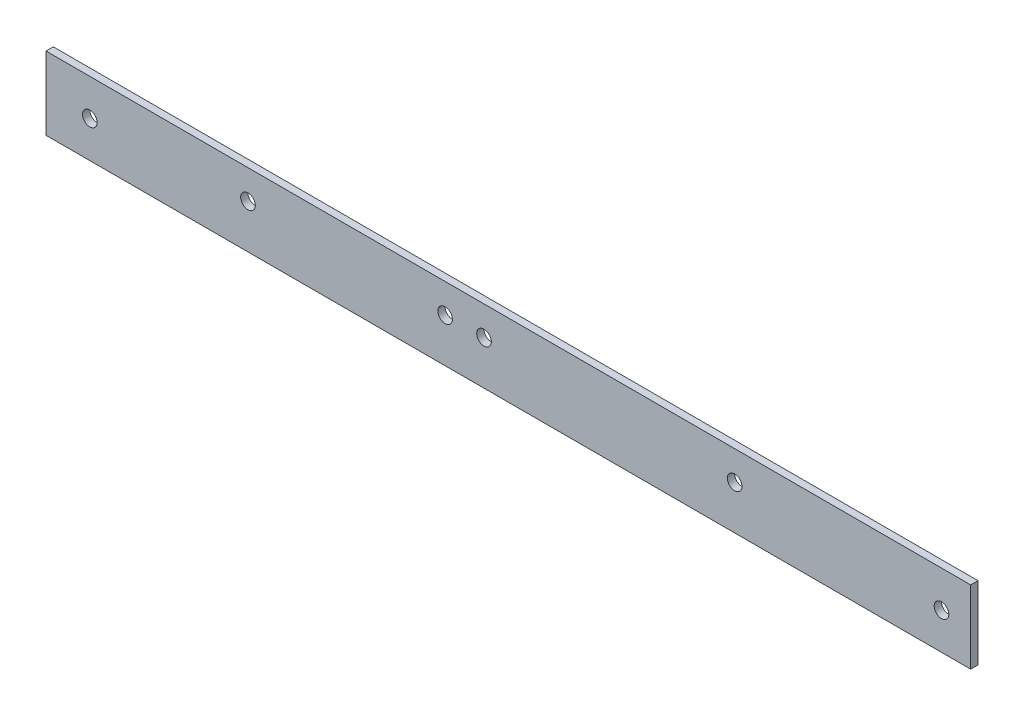
SolidWorks part; units mm, degrees
ref_plane "Plan de face" through (0, 0, 0) normal (0, 0, 1) x (1, 0, 0)
ref_plane "Plan de dessus" through (0, 0, 0) normal (0, 1, 0) x (1, 0, 0)
ref_plane "Plan de droite" through (0, 0, 0) normal (1, 0, 0) x (0, 0, -1)
sketch "Esquisse1" plane through (0, 0, 0) normal (0, 0, 1) x (1, 0, 0)
  line L0 (-50.3845, 16.9536) -> (120.2826, 16.9536) construction
  line L1 (-57.8845, 22.9536) -> (132.1155, 22.9536)
  line L2 (-57.8845, 22.9536) -> (-57.8845, 7.9536)
  line L3 (-57.8845, 7.9536) -> (132.1155, 7.9536)
  line L4 (132.1155, 22.9536) -> (132.1155, 7.9536)
  circle A0 centre (-48.8845, 15.4536) radius 1.5
  circle A1 centre (126.1155, 15.4536) radius 1.5
  circle A2 centre (-16.3845, 16.9536) radius 1.5
  circle A3 centre (83.6155, 16.9536) radius 1.5
  circle A4 centre (32.1155, 16.9536) radius 1.5
  circle A5 centre (24.1155, 16.9536) radius 1.5
  dimension "D3" = 6
  dimension "D5" = 6
  dimension "D7" = 41.5
  dimension "D9" = 9
  dimension "D11" = 90
  dimension "D12" = 8
  dimension "D1" = 190
  dimension "D2" = 15
  dimension "D4" = 7.5
  dimension "D6" = 7.5
  dimension "D8" = 141.5
  dimension "D10" = 7.5
extrude "Extrusion1" add sketch "Esquisse1" along normal blind 1.5
